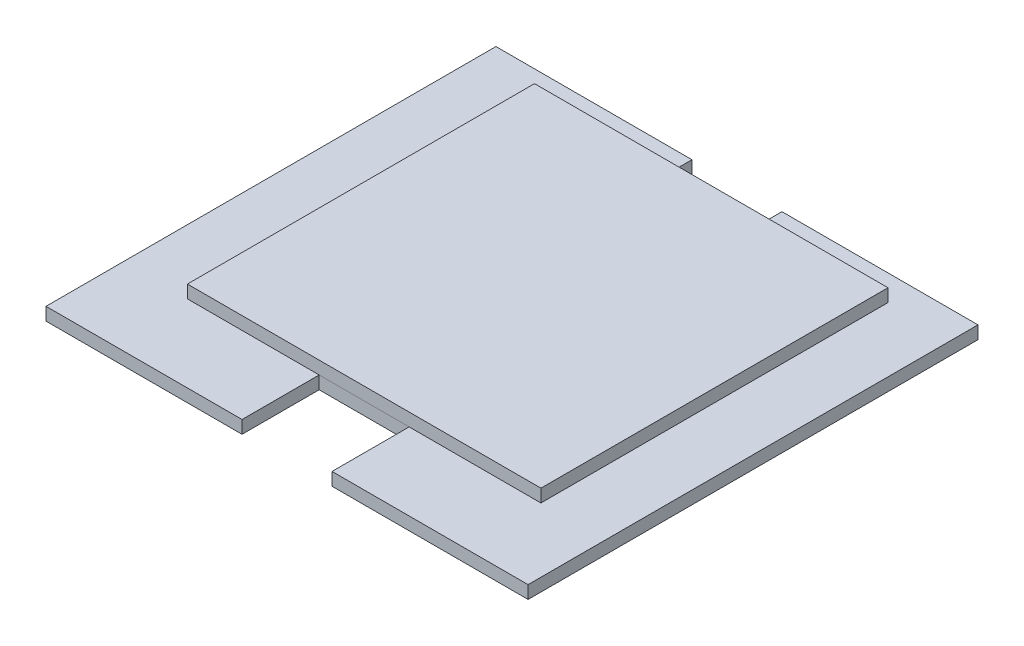
SolidWorks part; units mm, degrees
ref_plane "Front Plane" through (0, 0, 0) normal (0, 0, 1) x (1, 0, 0)
ref_plane "Top Plane" through (0, 0, 0) normal (0, 1, 0) x (1, 0, 0)
ref_plane "Right Plane" through (0, 0, 0) normal (1, 0, 0) x (0, 0, -1)
sketch "Sketch1" plane through (0, 0, 0) normal (0, 1, 0) x (1, 0, 0)
  line L0 (7, 35) -> (37.5, 35)
  line L1 (-37.5, -35) -> (-7, -35)
  line L2 (-37.5, -35) -> (-37.5, 35)
  line L3 (-37.5, 35) -> (-7, 35)
  line L4 (37.5, -35) -> (37.5, 35)
  line L5 (-37.5, -35) -> (37.5, 35) construction
  line L6 (-37.5, 35) -> (37.5, -35) construction
  line L8 (-7, -35) -> (-7, -23)
  line L9 (-7, -23) -> (7, -23)
  line L10 (7, -35) -> (7, -23)
  line L12 (-7, 35) -> (-7, 31)
  line L13 (-7, 31) -> (7, 31)
  line L14 (7, 35) -> (7, 31)
  line L15 (0, 31) -> (0, 0) construction
  line L16 (7, -35) -> (37.5, -35)
  point P0 (0, 0)
  dimension "D1" = 75
  dimension "D2" = 70
  dimension "D3" = 14
  dimension "D4" = 14
  dimension "D5" = 12
  dimension "D6" = 4
extrude "Boss-Extrude1" add sketch "Sketch1" along normal blind 2
sketch "Sketch2" plane through (0, 2, 0) normal (0, 1, 0) x (1, 0, 0)
  line L0 (7, 31) -> (-7, 31) construction
  line L1 (-27.5, -23) -> (27.5, -23)
  line L2 (-27.5, -23) -> (-27.5, 31)
  line L3 (-27.5, 31) -> (27.5, 31)
  line L4 (27.5, -23) -> (27.5, 31)
  line L5 (0, 0) -> (0, 31) construction
  line L6 (-7, -23) -> (7, -23) construction
  dimension "D1" = 55
extrude "Boss-Extrude2" add sketch "Sketch2" along normal blind 2 separate body
